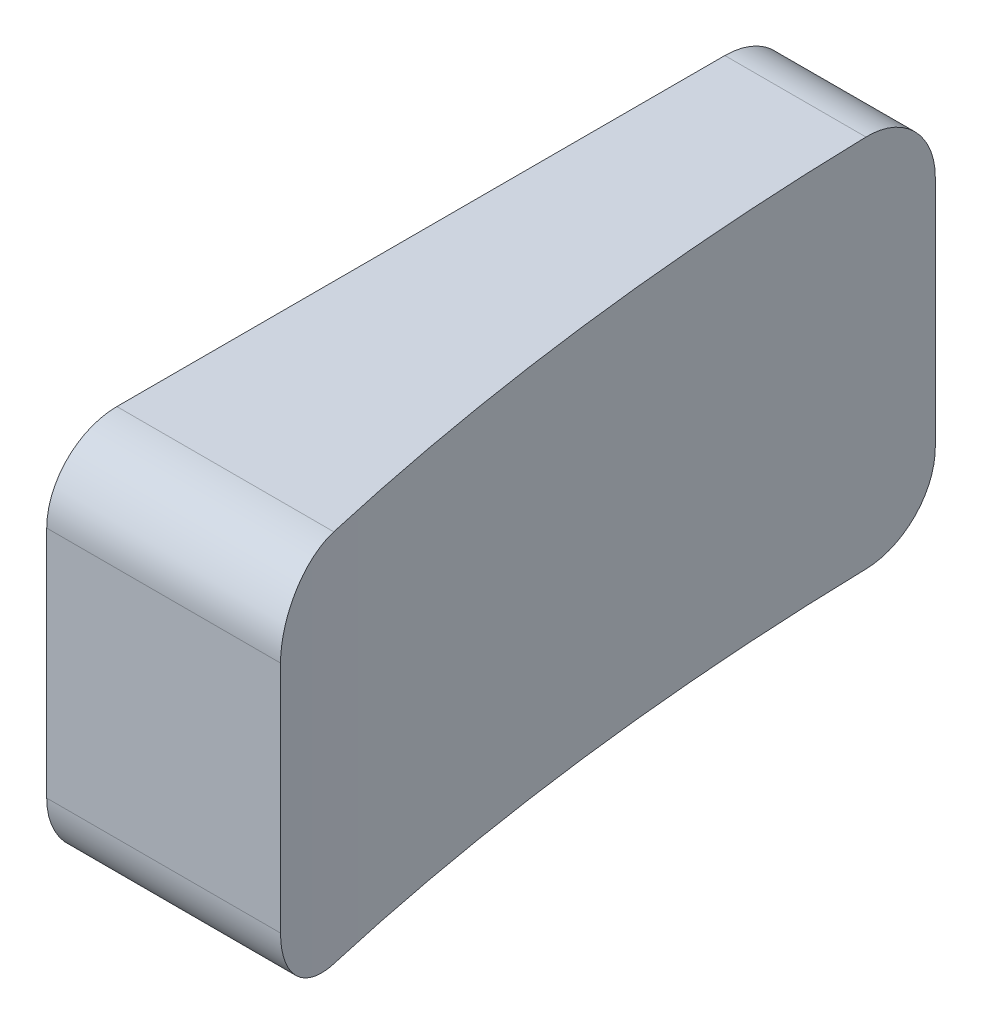
SolidWorks part; units mm, degrees
ref_plane "Front Plane" through (0, 0, 0) normal (0, 0, 1) x (1, 0, 0)
ref_plane "Top Plane" through (0, 0, 0) normal (0, 1, 0) x (1, 0, 0)
ref_plane "Right Plane" through (0, 0, 0) normal (1, 0, 0) x (0, 0, -1)
sketch "Sketch1" plane through (0, 0, 0) normal (0, 1, 0) x (1, 0, 0)
  line L0 (0, -25.4) -> (0, 25.4)
  line L1 (0, 25.4) -> (9.525, 25.4)
  line L2 (0, -25.4) -> (15.875, -25.4)
  line L3 (9.525, 25.4) -> (9.525, 59.6082) construction
  arc A0 (9.525, 25.4) -> (15.875, -25.4) centre (215.9, 25.4) ccw
  point P4 (0, 0)
  dimension "D1" = 9.525
  dimension "D2" = 50.8
  dimension "D4" = 15.875
extrude "Boss-Extrude1" add sketch "Sketch1" along normal blind 25.4
fillet "Fillet1" radius 4.7625 4 edges at (4.7625, 0, -25.4) (7.9375, 0, 25.4) (4.7625, 25.4, -25.4) (7.9375, 25.4, 25.4)
